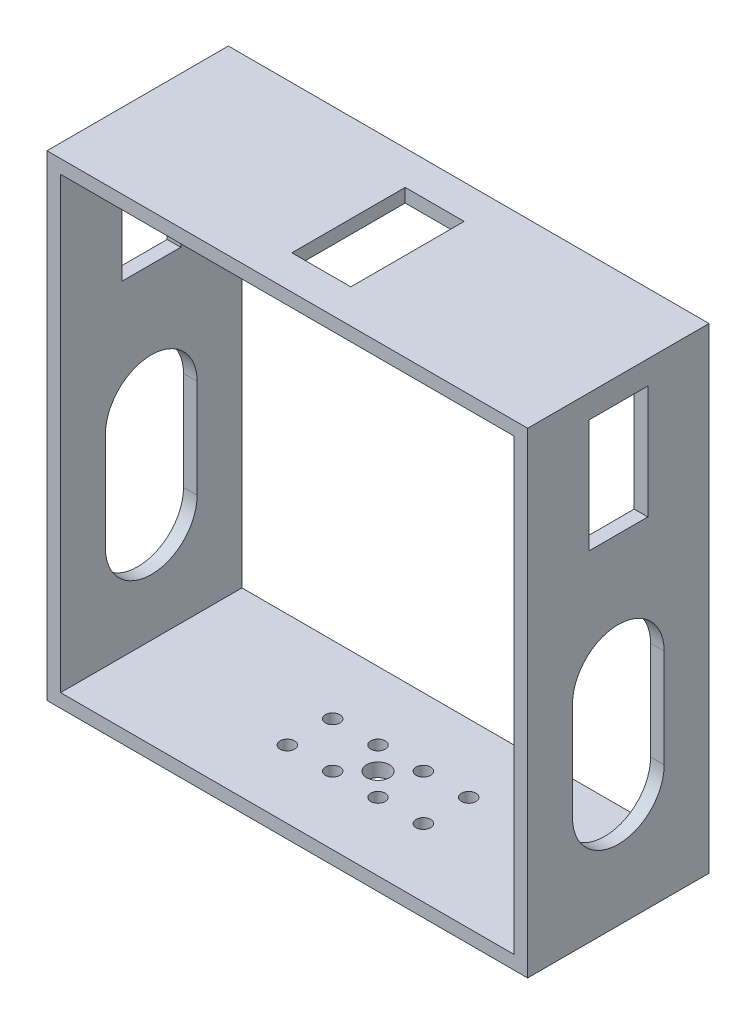
SolidWorks part; units mm, degrees
ref_plane "前视基准面" through (0, 0, 0) normal (0, 0, 1) x (1, 0, 0)
ref_plane "上视基准面" through (0, 0, 0) normal (0, 1, 0) x (1, 0, 0)
ref_plane "右视基准面" through (0, 0, 0) normal (1, 0, 0) x (0, 0, -1)
other "Configuration Table"
sketch "草图1" plane through (0, 0, 0) normal (0, 0, 1) x (1, 0, 0)
  line L0 (146.0665, 0) -> (-146.0665, 0) construction
  line L1 (0, -83.0601) -> (0, 83.0601) construction
  line L2 (28, 61.896) -> (-28, 61.896) construction
  line L3 (-28, 61.896) -> (-28, -91.7584) construction
  line L4 (28, 61.896) -> (28, -90.2615) construction
  line L15 (-53, 0) -> (-53, 105)
  line L16 (-53, 105) -> (53, 105)
  line L17 (53, 0) -> (53, 105)
  line L20 (-53, 0) -> (53, 0)
  point P0 (-28, 0)
  point P4 (0, 0)
  point P8 (0, 0)
  point P11 (0, 61.896)
  point P14 (28, 0)
  dimension "D1" = 106
extrude "凸台-拉伸1" add sketch "草图1" along normal blind 40
sketch "草图3" plane through (0, 0, 0) normal (0, 0, -1) x (-1, 0, 0)
  line L0 (0, 0) -> (0, 165.1711) construction
  line L1 (0, 0) -> (-121.8649, 0) construction
  line L2 (-50, 105) -> (-50, 102) construction
  line L3 (-53, 105) -> (53, 105) construction
  line L4 (-53, 0) -> (-53, 105) construction
  line L5 (-23.3554, 105) -> (-23.3554, 0) construction
  line L6 (-23.3554, 52.5) -> (-117.2398, 52.5) construction
  line L7 (50, 105) -> (50, 102) construction
  line L8 (50, 0) -> (50, 3) construction
  line L9 (-50, 0) -> (-50, 3) construction
  line L10 (53, 0) -> (-53, 0) construction
  line L11 (-50, 102) -> (50, 102)
  line L12 (-50, 102) -> (-50, 3)
  line L13 (-50, 3) -> (50, 3)
  line L14 (50, 102) -> (50, 3)
  dimension "D1" = 3
  dimension "D2" = 3
sketch "草图8" plane through (-53, 0, 0) normal (-1, 0, 0) x (0, 0, 1)
  line L0 (22.5, 130.575) -> (17.5, 130.575) construction
  line L1 (20, 105) -> (20, 141) construction
  line L2 (20, 141) -> (20, 132.5) construction
  line L6 (20, 141) -> (20, 113) construction
  line L8 (17.5, 130.575) -> (17.5, 127.601) construction
  line L9 (22.5, 130.575) -> (22.5, 127.601) construction
  line L10 (22.5, 127.601) -> (17.5, 127.601) construction
  line L11 (40, 105) -> (0, 105) construction
  circle A7 centre (20, 141) radius 1
  circle A8 centre (20, 113) radius 1
  circle A9 centre (20, 132.5) radius 5.5 construction
  arc A10 (17.5, 127.601) -> (22.5, 127.601) centre (20, 132.5) cw
  arc A11 (17.5, 127.601) -> (22.5, 127.601) centre (20, 127.1286) ccw
  point P10 (20, 130.575)
extrude "切除-拉伸1" cut sketch "草图3" against normal through all both and the other way through all
sketch "草图7" plane through (0, 0, 0) normal (0, -1, 0) x (1, 0, 0)
  line L0 (-53, 20) -> (53, 20) construction
  line L1 (-53, 40) -> (-53, 0) construction
  line L2 (53, 40) -> (53, 0) construction
  line L3 (0, 40) -> (0, 0) construction
  line L4 (-53, 40) -> (53, 40) construction
  line L5 (5, 25) -> (15, 25) construction
  line L6 (-5, 15) -> (5, 15) construction
  line L7 (-5, 15) -> (-5, 25) construction
  line L8 (-5, 25) -> (5, 25) construction
  line L9 (5, 15) -> (5, 25) construction
  line L10 (0, 25) -> (0, 15) construction
  line L11 (-5, 20) -> (5, 20) construction
  circle A0 centre (0, 20) radius 2.5
  circle A1 centre (5, 25) radius 1.6
  circle A2 centre (5, 15) radius 1.6
  circle A3 centre (-5, 15) radius 1.6
  circle A4 centre (-5, 25) radius 1.6
  circle A5 centre (15, 25) radius 1.6
  circle A6 centre (-15, 25) radius 1.6
  circle A7 centre (15, 15) radius 1.6
  circle A8 centre (-15, 15) radius 1.6
extrude "切除-拉伸3" cut sketch "草图7" against normal blind 3 and the other way blind 1
sketch "草图6" plane through (0, 105, 0) normal (0, 1, 0) x (1, 0, 0)
  line L0 (0, 0) -> (0, -40) construction
  line L1 (-53, -20) -> (53, -20) construction
  line L3 (53, -40) -> (53, 0) construction
  line L4 (53, -40) -> (-53, -40) construction
  line L9 (0, -16.2741) -> (0, -37.4626) construction
  line L12 (6.5, -32.5) -> (-6.5, -32.5)
  line L13 (6.5, -32.5) -> (6.5, -7.5)
  line L14 (6.5, -7.5) -> (-6.5, -7.5)
  line L15 (-6.5, -32.5) -> (-6.5, -7.5)
  line L16 (0, -7.5) -> (0, -32.5) construction
  line L17 (6.5, -20) -> (-6.5, -20) construction
  point P5 (0, -20)
extrude "切除-拉伸4" cut sketch "草图6" against normal up to next and the other way through all
sketch "草图10" plane through (-53, 0, 0) normal (-1, 0, 0) x (0, 0, 1)
  line L0 (20, 0) -> (20, 160.7067) construction
  line L1 (40, 0) -> (0, 0) construction
  line L2 (35.1632, 99.807) -> (4.8368, 99.807) construction
  line L3 (20, 101.807) -> (29.1345, 101.807) construction
  line L4 (26.5, 74.807) -> (13.5, 74.807)
  line L5 (26.5, 74.807) -> (26.5, 99.807)
  line L6 (26.5, 99.807) -> (13.5, 99.807)
  line L7 (13.5, 74.807) -> (13.5, 99.807)
  line L8 (20, 99.807) -> (20, 74.807) construction
  line L9 (26.5, 87.307) -> (13.5, 87.307) construction
  point P4 (20, 87.307)
  point P7 (20, 99.807)
  dimension "D1" = 25
  dimension "D2" = 2
extrude "切除-拉伸5" cut sketch "草图10" against normal through all both and the other way through all
sketch "草图12" plane through (53, 0, 0) normal (1, 0, 0) x (0, 0, -1)
  line L0 (-20, 0) -> (-20, 69.2078) construction
  line L1 (-40, 0) -> (0, 0) construction
  line L2 (-20, 25.65) -> (-20, 47.3985) construction
  line L3 (-30.1086, 25.65) -> (-30.1086, 47.3985)
  line L4 (-9.8914, 25.65) -> (-9.8914, 47.3985)
  arc A0 (-30.1086, 25.65) -> (-9.8914, 25.65) centre (-20, 25.65) ccw
  arc A1 (-9.8914, 47.3985) -> (-30.1086, 47.3985) centre (-20, 47.3985) ccw
  point P6 (-20, 36.5242)
extrude "切除-拉伸6" cut sketch "草图12" against normal through all both and the other way through all
